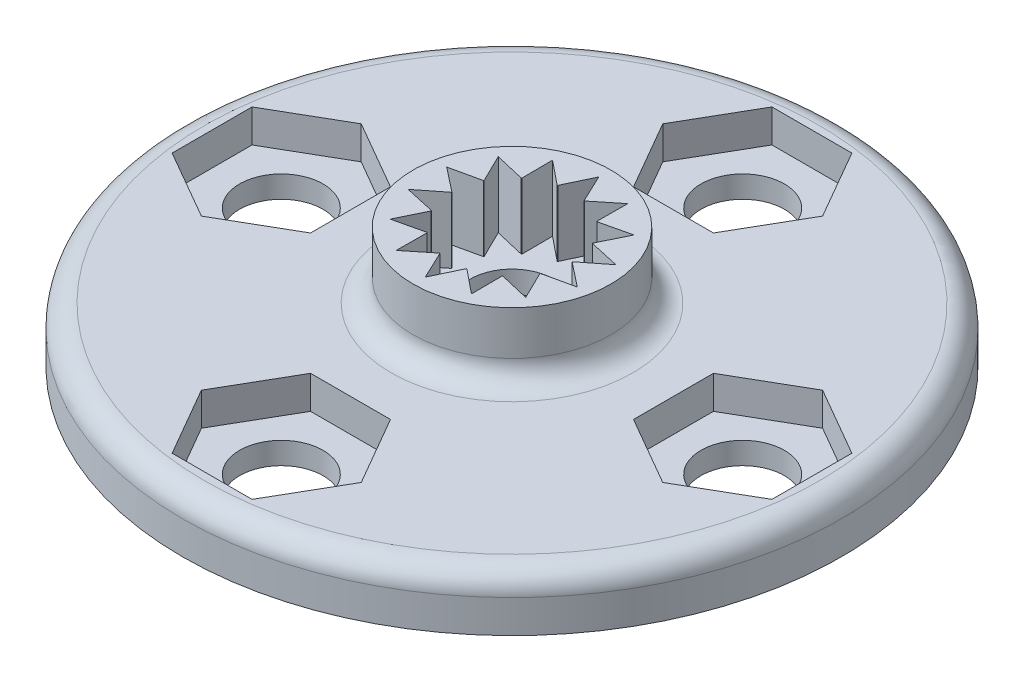
SolidWorks part; units mm, degrees
ref_plane "Alzado" through (0, 0, 0) normal (0, 0, 1) x (1, 0, 0)
ref_plane "Planta" through (0, 0, 0) normal (0, 1, 0) x (1, 0, 0)
ref_plane "Vista lateral" through (0, 0, 0) normal (1, 0, 0) x (0, 0, -1)
sketch "Croquis1" plane through (0, 0, 0) normal (0, 1, 0) x (1, 0, 0)
  circle A0 centre (0, 0) radius 15
  dimension "D1" = 30
extrude "Saliente-Extruir1" add sketch "Croquis1" along normal blind 2.5
sketch "Croquis2" plane through (0, 2.5, 0) normal (0, 1, 0) x (1, 0, 0)
  circle A0 centre (0, 0) radius 4.5
  dimension "D1" = 9
extrude "Saliente-Extruir2" add sketch "Croquis2" along normal blind 3
sketch "Croquis3" plane through (0, 5.5, 0) normal (0, 1, 0) x (1, 0, 0)
  circle A0 centre (0, 0) radius 2.75
  dimension "D1" = 5.5
extrude "Cortar-Extruir1" cut sketch "Croquis3" against normal blind 3
sketch "Croquis4" plane through (0, 0, 0) normal (0, -1, 0) x (1, 0, 0)
  circle A0 centre (0, 0) radius 1.9
  dimension "D1" = 3.8
extrude "Cortar-Extruir2" cut sketch "Croquis4" against normal up to next
sketch "Croquis6" plane through (0, 2.5, 0) normal (0, 1, 0) x (1, 0, 0)
  circle A0 centre (0, 0) radius 10.5 construction
  circle A1 centre (0, 10.5) radius 1.9
  dimension "D1" = 3.8
  dimension "D2" = 21
extrude "Cortar-Extruir4" cut sketch "Croquis6" against normal up to next
sketch "Croquis5" plane through (0, 2.5, 0) normal (0, 1, 0) x (1, 0, 0)
  line L0 (0, 10.5) -> (0, 15) construction
  line L1 (-1.8187, 13.65) -> (-3.6373, 10.5)
  line L2 (-3.6373, 10.5) -> (-1.8187, 7.35)
  line L3 (-1.8187, 7.35) -> (1.8187, 7.35)
  line L4 (1.8187, 7.35) -> (3.6373, 10.5)
  line L5 (3.6373, 10.5) -> (1.8187, 13.65)
  line L6 (1.8187, 13.65) -> (-1.8187, 13.65)
  circle A1 centre (0, 10.5) radius 3.15 construction
  circle A2 centre (0, 10.5) radius 1.9 construction
  circle A3 centre (0, 0) radius 15 construction
  point P13 (0, 13.65)
  dimension "D1" = 6.3
extrude "Cortar-Extruir3" cut sketch "Croquis5" against normal offset from surface 1 and the other way blind 1 up to face at (0, 0, -8.6)
pattern_circular "MatrizC1" count 4 over 360 about axis through (0, 0, 0) along (0, 1, 0) of "Cortar-Extruir3", "Cortar-Extruir4"
sketch "Croquis7" plane through (0, 5.5, 0) normal (0, 1, 0) x (1, 0, 0)
  line L0 (-0.6, 2.6837) -> (0.6, 2.6837) construction
  line L1 (0, 2.75) -> (0, 3.95) construction
  line L2 (0, 3.95) -> (0.6, 2.6837)
  line L3 (0, 3.95) -> (-0.6, 2.6837)
  arc A0 (0.6, 2.6837) -> (-0.6, 2.6837) centre (0, 0) ccw
  circle A1 centre (0, 0) radius 2.75 construction
  point P5 (0, 2.75)
  point P8 (0, 2.6837)
  dimension "D1" = 1.2
  dimension "D2" = 1.2
extrude "Cortar-Extruir5" cut sketch "Croquis7" against normal up to surface (3 mm away) up to face at (0, 2.5, 1.9)
pattern_circular "MatrizC2" count 14 over 360 about axis through (0, 0, 0) along (0, 1, 0) of "Cortar-Extruir5"
fillet "Redondeo1" radius 1 2 edges at (0, 2.5, 4.5) (0, 2.5, 15)
sketch "Croquis9" plane through (0, 0, 0) normal (0, -1, 0) x (1, 0, 0)
  circle A0 centre (0, 0) radius 3.2
  dimension "D1" = 6.4
extrude "Cortar-Extruir6" cut sketch "Croquis9" against normal blind 1.5
